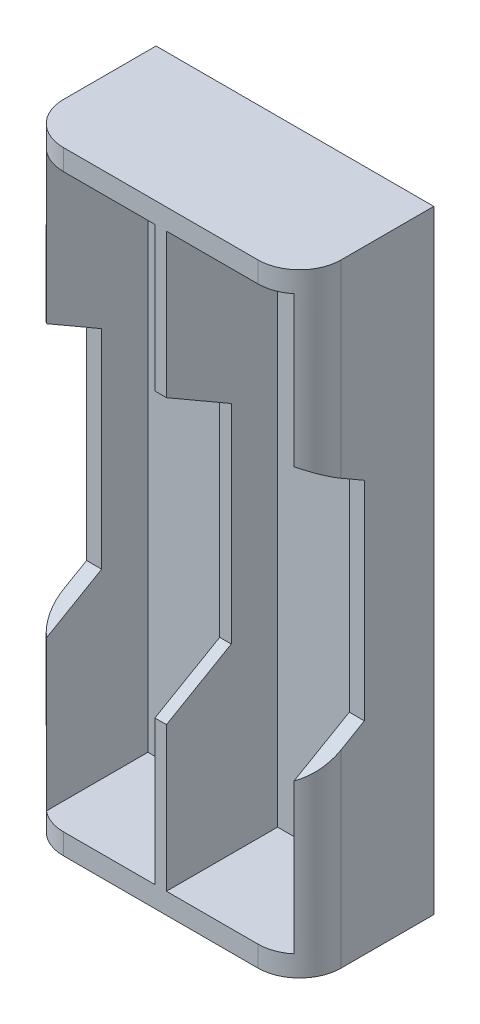
SolidWorks part; units mm, degrees
ref_plane "Front" through (0, 0, 0) normal (0, 0, 1) x (1, 0, 0)
ref_plane "Top" through (0, 0, 0) normal (0, 1, 0) x (1, 0, 0)
ref_plane "Right" through (0, 0, 0) normal (1, 0, 0) x (0, 0, -1)
sketch "Sketch1" plane through (0, 0, 0) normal (0, 0, 1) x (1, 0, 0)
  line L1 (-12, -26.5) -> (12, -26.5)
  line L2 (-12, -26.5) -> (-12, 26.5)
  line L3 (-12, 26.5) -> (12, 26.5)
  line L4 (12, -26.5) -> (12, 26.5)
  line L5 (-12, -26.5) -> (12, 26.5) construction
  line L6 (-12, 26.5) -> (12, -26.5) construction
  point P0 (0, 0)
  dimension "D1" = 53
  dimension "D2" = 24
extrude "Boss-Extrude1" add sketch "Sketch1" along normal blind 2
sketch "Sketch2" plane through (0, -26.5, 0) normal (0, -1, 0) x (1, 0, 0)
  line L0 (-8.4, 11.6) -> (8.4, 11.6)
  line L1 (0, 0) -> (0, 11.6) construction
  line L2 (-12, 0) -> (12, 0) construction
  line L3 (-12, 2) -> (-12, 8)
  line L4 (-12, 2) -> (12, 2)
  line L5 (-12, 2) -> (12, 2) construction
  line L6 (12, 2) -> (12, 8)
  arc A0 (-12, 8) -> (-8.4, 11.6) centre (-8.4, 8) cw
  arc A1 (12, 8) -> (8.4, 11.6) centre (8.4, 8) ccw
  point P17 (0, 2)
  dimension "D1" = 11.6
  dimension "D2" = 8
extrude "Boss-Extrude2" add sketch "Sketch2" against normal up to surface (53 mm away) up to face at (0, 26.5, 1)
sketch "Sketch3" plane through (0, 0, 11.6) normal (0, 0, 1) x (1, 0, 0)
  line L0 (-8.4, 26.5) -> (8.4, 26.5) construction
  line L1 (0.5, 24.7) -> (10.7, 24.7)
  line L2 (0.5, 24.7) -> (0.5, -24.7)
  line L3 (0.5, -24.7) -> (10.7, -24.7)
  line L4 (10.7, 24.7) -> (10.7, -24.7)
  line L5 (0, 0) -> (0.5, 0) construction
  line L6 (-0.5, 24.7) -> (-0.5, -24.7)
  line L7 (-0.5, -24.7) -> (-10.7, -24.7)
  line L8 (8.4, -26.5) -> (-8.4, -26.5) construction
  line L10 (-10.7, 24.7) -> (-10.7, -24.7)
  line L11 (-0.5, 24.7) -> (-10.7, 24.7)
  line L13 (0, 0) -> (0, -26.5) construction
  point P0 (0, 0)
  dimension "D1" = 10.2
  dimension "D2" = 1.8
  dimension "D3" = 0.5
extrude "Cut-Extrude1" cut sketch "Sketch3" against normal offset from surface (9.6 mm away) 2 up to face at (0, 0, 0)
sketch "Sketch4" plane through (0, 0, 0) normal (1, 0, 0) x (0, 0, -1)
  line L0 (0, 0) -> (-16.6, 0) construction
  line L1 (-16.6, -15.1199) -> (-16.6, 15.1199)
  line L2 (-16.6, 15.1199) -> (-6, 9)
  line L3 (-6, 9) -> (-6, -9)
  line L4 (-16.6, -15.1199) -> (-6, -9)
  line L5 (0, -26.5) -> (0, 26.5) construction
  line L6 (-11.6, 26.5) -> (-11.6, 24.7) construction
  point P7 (-6, 0)
  dimension "D1" = 6
  dimension "D2" = 18
  dimension "D3" = 60
  dimension "D4" = 5
extrude "Cut-Extrude2" cut sketch "Sketch4" against normal through all both and the other way through all
